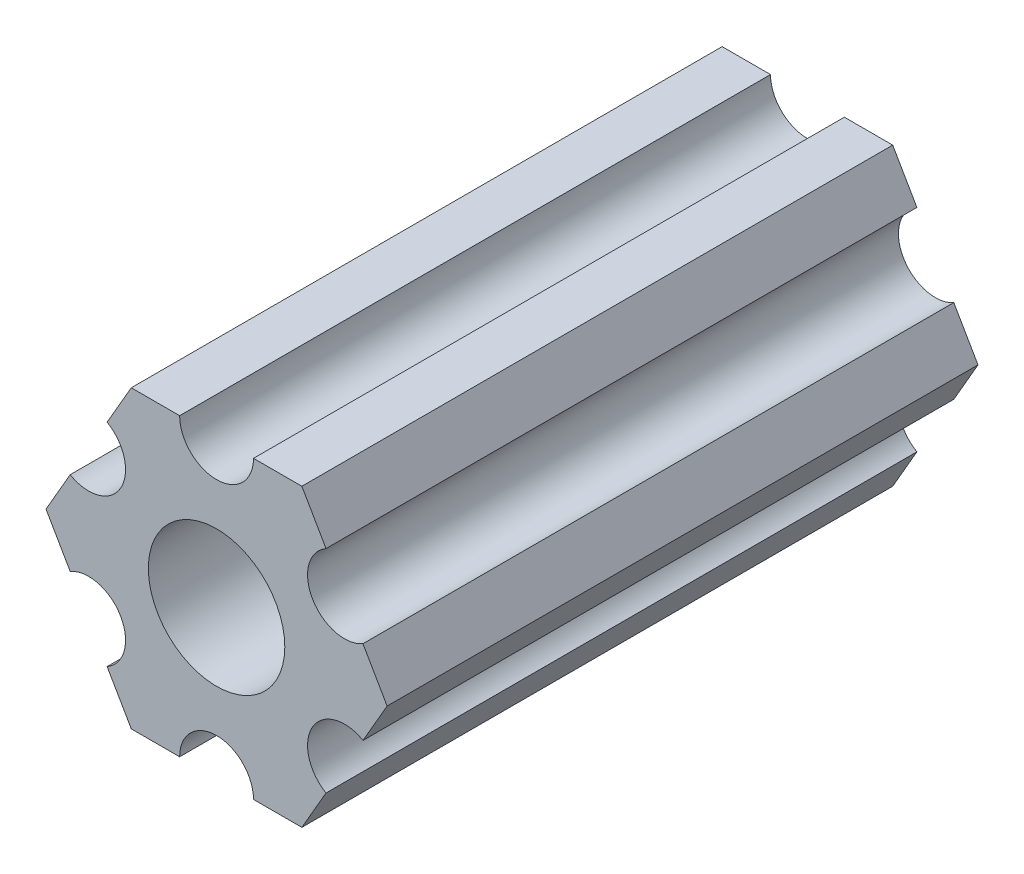
SolidWorks part; units mm, degrees
ref_plane "Front Plane" through (0, 0, 0) normal (0, 0, 1) x (1, 0, 0)
ref_plane "Top Plane" through (0, 0, 0) normal (0, 1, 0) x (1, 0, 0)
ref_plane "Right Plane" through (0, 0, 0) normal (1, 0, 0) x (0, 0, -1)
ref_plane "Plane1" through (0, 0, 0) normal (0, 0, -1) x (-1, 0, 0)
sketch "Sketch1" plane through (0, 0, 0) normal (0, 0, -1) x (-1, 0, 0)
  line L0 (-4.7055, -4.5498) -> (-3.6662, -6.35)
  line L1 (-3.6662, -6.35) -> (-1.5875, -6.35)
  line L2 (1.5875, -6.35) -> (3.6662, -6.35)
  line L3 (3.6662, -6.35) -> (4.7055, -4.5498)
  line L4 (6.293, -1.8002) -> (7.3323, 0)
  line L5 (7.3323, 0) -> (6.293, 1.8002)
  line L6 (4.7055, 4.5498) -> (3.6662, 6.35)
  line L7 (3.6662, 6.35) -> (1.5875, 6.35)
  line L8 (-1.5875, 6.35) -> (-3.6662, 6.35)
  line L9 (-3.6662, 6.35) -> (-4.7055, 4.5498)
  line L10 (-6.293, 1.8002) -> (-7.3323, 0)
  line L11 (-7.3323, 0) -> (-6.293, -1.8002)
  circle A0 centre (0, 0) radius 2.9337
  arc A1 (-6.293, -1.8002) -> (-4.7055, -4.5498) centre (-5.4993, -3.175) cw
  arc A2 (-1.5875, -6.35) -> (1.5875, -6.35) centre (0, -6.35) cw
  arc A3 (4.7055, -4.5498) -> (6.293, -1.8002) centre (5.4993, -3.175) cw
  arc A4 (6.293, 1.8002) -> (4.7055, 4.5498) centre (5.4993, 3.175) cw
  arc A5 (1.5875, 6.35) -> (-1.5875, 6.35) centre (0, 6.35) cw
  arc A6 (-4.7055, 4.5498) -> (-6.293, 1.8002) centre (-5.4993, 3.175) cw
extrude "Boss-Extrude1" add sketch "Sketch1" along normal blind 25.4
